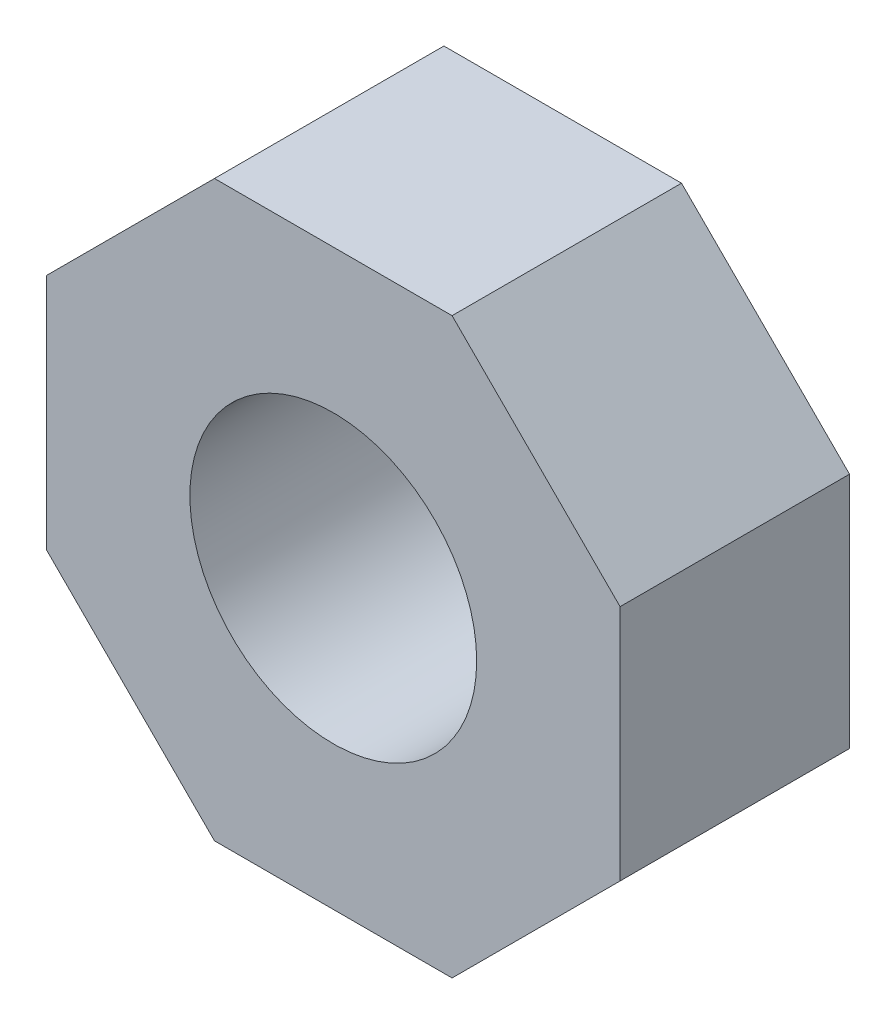
SolidWorks part; units mm, degrees
ref_plane "Plan de face" through (0, 0, 0) normal (0, 0, 1) x (1, 0, 0)
ref_plane "Plan de dessus" through (0, 0, 0) normal (0, 1, 0) x (1, 0, 0)
ref_plane "Plan de droite" through (0, 0, 0) normal (1, 0, 0) x (0, 0, -1)
sketch "Esquisse1" plane through (0, 0, 0) normal (0, 0, 1) x (1, 0, 0)
  line L0 (0, 0) -> (5, 0) construction
  line L1 (5, 0) -> (-5, 0) construction
  line L2 (-3.5355, -3.5355) -> (-2.0711, -5)
  line L3 (5, 5) -> (5, -5) construction
  line L4 (-5, -5) -> (5, 5) construction
  line L5 (5, 5) -> (-5, 5) construction
  line L6 (0, 0) -> (0, 5) construction
  line L7 (0, 5) -> (0, -5) construction
  line L8 (5, -5) -> (-5, 5) construction
  line L9 (0, 0) -> (-3.5355, -3.5355) construction
  line L10 (-3.5355, -3.5355) -> (0, 0) construction
  line L11 (0, 0) -> (3.5355, -3.5355) construction
  line L12 (-5, 5) -> (0, 5) construction
  line L13 (0, 5) -> (5, 5) construction
  line L15 (5, -5) -> (-5, -5) construction
  line L16 (-5, -5) -> (-5, 5) construction
  line L17 (3.5355, -3.5355) -> (0, 0) construction
  line L18 (0, 0) -> (3.5355, 3.5355) construction
  line L19 (3.5355, 3.5355) -> (0, 0) construction
  line L20 (0, 0) -> (-3.5355, 3.5355) construction
  line L21 (3.5355, 3.5355) -> (2.0711, 5)
  line L22 (-2.0711, -5) -> (2.0711, -5)
  line L23 (-3.5355, -3.5355) -> (-5, -2.0711)
  line L24 (2.0711, 5) -> (5, 2.0711)
  line L25 (3.5355, -3.5355) -> (5, -2.0711)
  line L26 (5, -2.0711) -> (2.0711, -5)
  line L27 (-5, -2.0711) -> (-5, 0)
  line L28 (-3.5355, 3.5355) -> (-5, 2.0711)
  line L29 (-5, 2.0711) -> (-5, 0)
  line L30 (-2.0711, 5) -> (2.0711, 5)
  line L31 (5, 2.0711) -> (5, -2.0711)
  line L32 (5, -2.0711) -> (2.0711, -5)
  line L33 (-3.5355, 3.5355) -> (-2.0711, 5)
  line L34 (5, 2.0711) -> (5, -2.0711)
  circle A0 centre (0, 0) radius 5 construction
  circle A1 centre (0, 0) radius 2.5
extrude "Boss.-Extru.1" add sketch "Esquisse1" along normal blind 4
